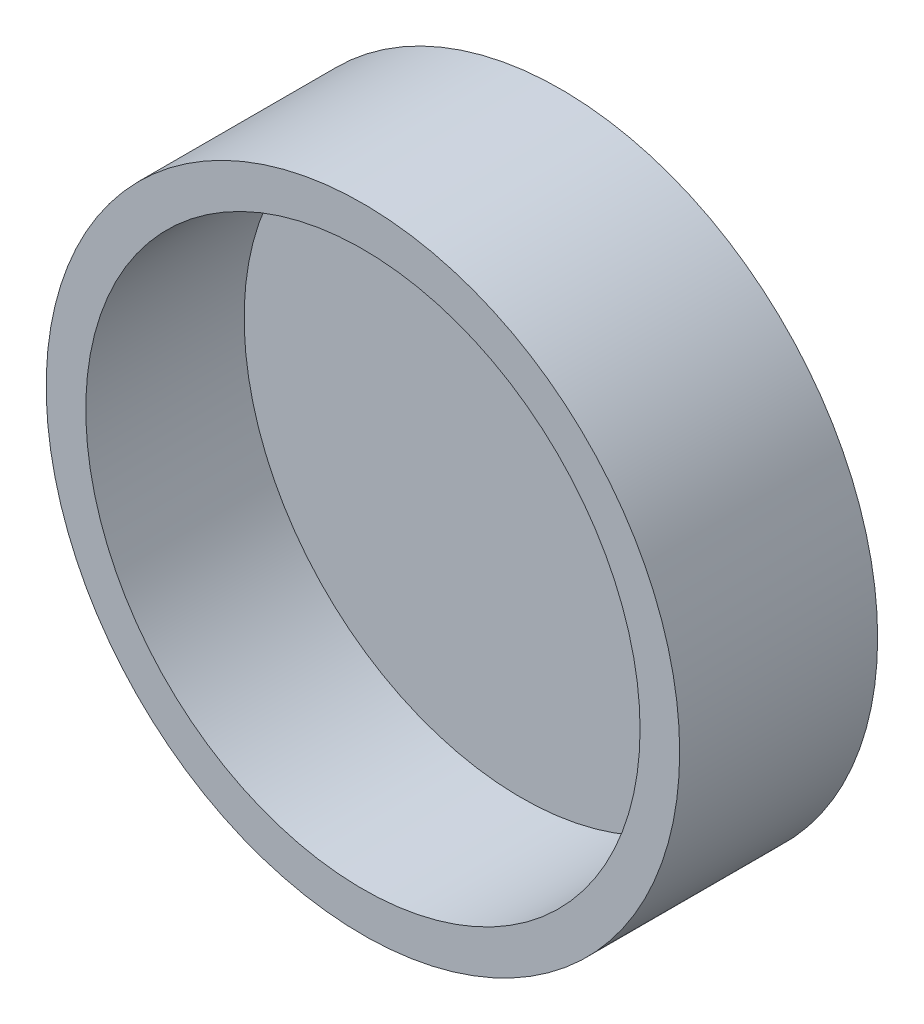
SolidWorks part; units mm, degrees
ref_plane "Front Plane" through (0, 0, 0) normal (0, 0, 1) x (1, 0, 0)
ref_plane "Top Plane" through (0, 0, 0) normal (0, 1, 0) x (1, 0, 0)
ref_plane "Right Plane" through (0, 0, 0) normal (1, 0, 0) x (0, 0, -1)
sketch "Sketch1" plane through (0, 0, 0) normal (0, 0, 1) x (1, 0, 0)
  circle A0 centre (0, 0) radius 35
  dimension "D1" = 70
extrude "Boss-Extrude1" add sketch "Sketch1" along normal blind 20
shell "Shell1" thickness 5
